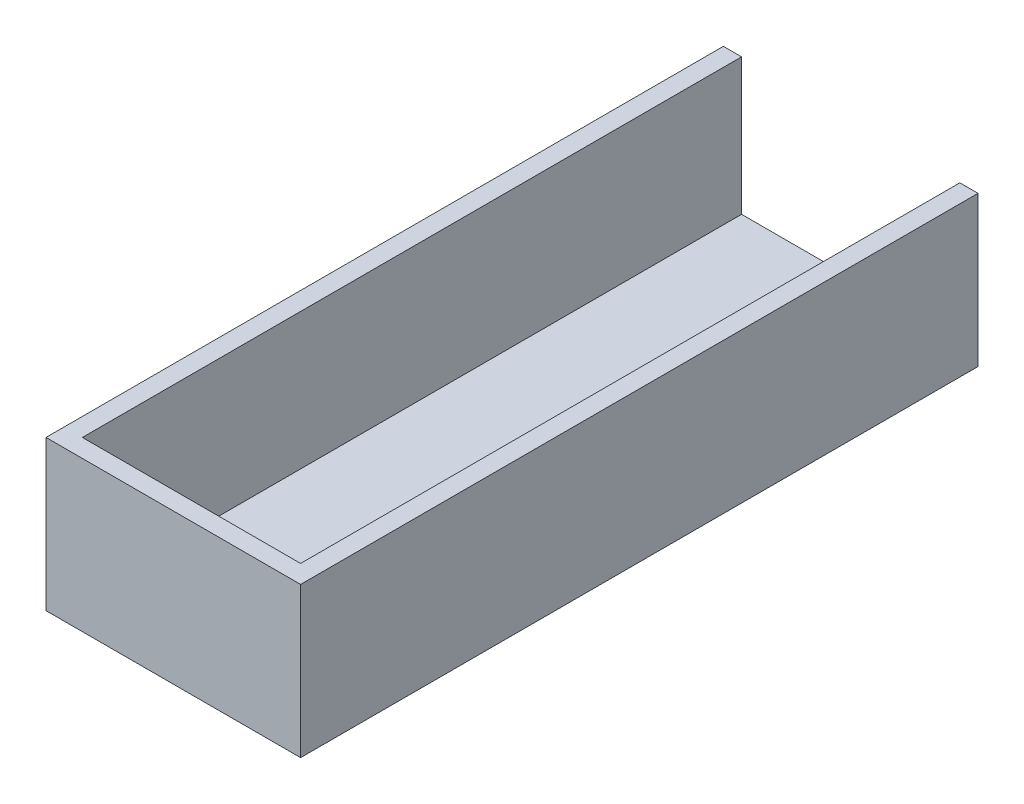
SolidWorks part; units mm, degrees
ref_plane "Alzado" through (0, 0, 0) normal (0, 0, 1) x (1, 0, 0)
ref_plane "Planta" through (0, 0, 0) normal (0, 1, 0) x (1, 0, 0)
ref_plane "Vista lateral" through (0, 0, 0) normal (1, 0, 0) x (0, 0, -1)
sketch "Croquis1" plane through (0, 0, 0) normal (0, 1, 0) x (1, 0, 0)
  line L0 (0, 0) -> (114.0103, 0) construction
  line L1 (0, 0) -> (0, -53.7026) construction
  line L3 (-28, 74.5) -> (28, 74.5)
  line L4 (-28, 74.5) -> (-28, -74.5)
  line L5 (-28, -74.5) -> (28, -74.5)
  line L6 (28, 74.5) -> (28, -74.5)
  line L7 (-28, 74.5) -> (28, -74.5) construction
  line L8 (-28, -74.5) -> (28, 74.5) construction
  point P4 (0, 0)
  dimension "D1" = 56
  dimension "D2" = 149
extrude "Saliente-Extruir4" add sketch "Croquis1" along normal blind 33
sketch "Croquis2" plane through (0, 33, 0) normal (0, 1, 0) x (1, 0, 0)
  line L1 (-24, -70.5) -> (24, -70.5)
  line L2 (-24, -70.5) -> (-24, 74.5)
  line L3 (-24, 74.5) -> (24, 74.5)
  line L4 (24, -70.5) -> (24, 74.5)
  point P4 (0, 0)
  point P6 (0, 0)
  point P7 (0, 0)
  dimension "D1" = 48
  dimension "D2" = 145
  dimension "D3" = 4
extrude "Cortar-Extruir1" cut sketch "Croquis2" against normal blind 30
